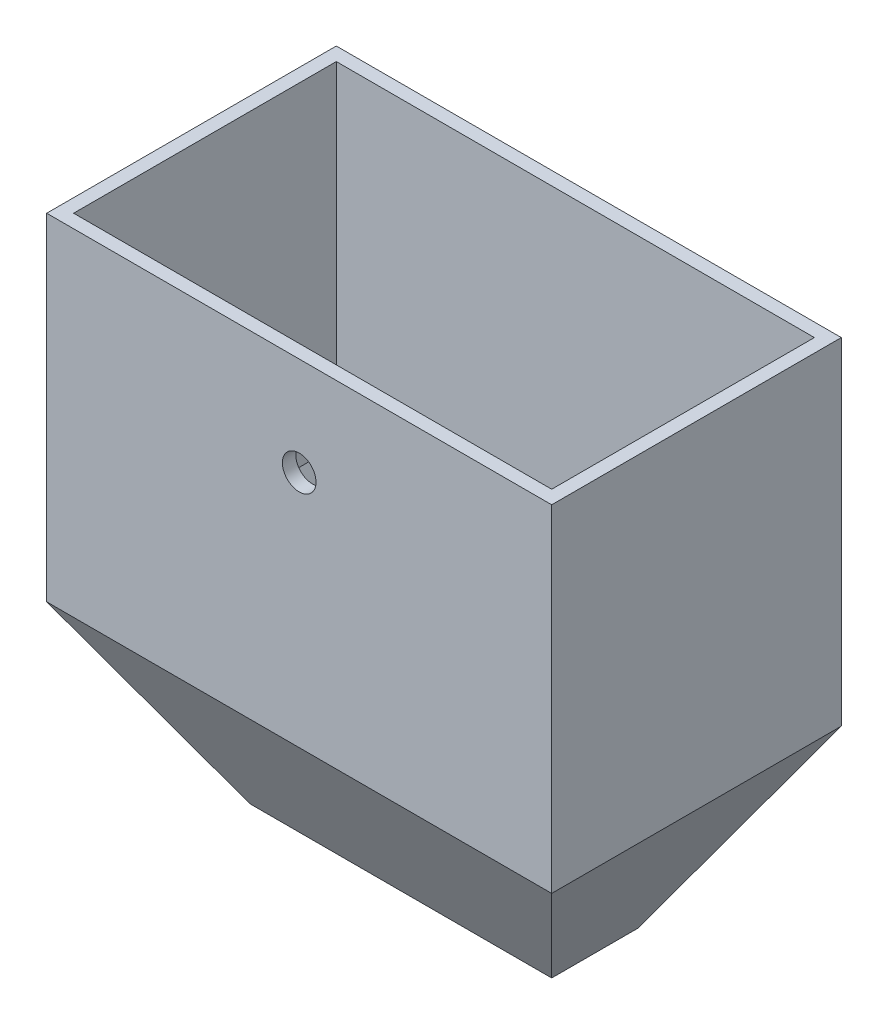
SolidWorks part; units mm, degrees
material "1.4511 (X3CrNb17)"
ref_plane "前视基准面" through (0, 0, 0) normal (0, 0, 1) x (1, 0, 0)
ref_plane "上视基准面" through (0, 0, 0) normal (0, 1, 0) x (1, 0, 0)
ref_plane "右视基准面" through (0, 0, 0) normal (1, 0, 0) x (0, 0, -1)
sketch "草图1" plane through (0, 0, 0) normal (0, 1, 0) x (1, 0, 0)
  line L1 (-187.57, 107.57) -> (187.57, 107.57)
  line L2 (-187.57, 107.57) -> (-187.57, -107.57)
  line L3 (-187.57, -107.57) -> (187.57, -107.57)
  line L4 (187.57, 107.57) -> (187.57, -107.57)
  line L5 (-187.57, 107.57) -> (187.57, -107.57) construction
  line L6 (-187.57, -107.57) -> (187.57, 107.57) construction
  point P1 (0, 0)
  dimension "D1" = 375.14
  dimension "D2" = 215.14
extrude "凸台-拉伸1" add sketch "草图1" along normal blind 250
ref_plane "基准面1" through (0, -130, 0) normal (0, 1, 0) x (1, 0, 0)
sketch "草图4" plane through (0, -130, 0) normal (0, 1, 0) x (1, 0, 0)
  line L1 (-112, 32) -> (112, 32)
  line L2 (-112, 32) -> (-112, -32)
  line L3 (-112, -32) -> (112, -32)
  line L4 (112, 32) -> (112, -32)
  line L5 (-112, 32) -> (112, -32) construction
  line L6 (-112, -32) -> (112, 32) construction
  point P0 (0, 0)
  dimension "D1" = 224
  dimension "D2" = 64
loft "放样1" add profiles "草图4" section face at (0, 0, 0) section "草图4"
shell "抽壳1" thickness 10
sketch "草图5" plane through (0, 0, 107.57) normal (0, 0, 1) x (1, 0, 0)
  line L0 (-187.57, 250) -> (187.57, 250) construction
  line L1 (-187.57, 250) -> (-187.57, 0) construction
  circle A0 centre (0, 177) radius 12.5
  dimension "D1" = 25
  dimension "D2" = 73
  dimension "D3" = 187.57
extrude "切除-拉伸1" cut sketch "草图5" against normal blind 10
sketch "草图6" plane through (0, -130, 0) normal (0, -1, 0) x (1, 0, 0)
  line L1 (-107, 27) -> (107, 27)
  line L2 (-107, 27) -> (-107, -27)
  line L3 (-107, -27) -> (107, -27)
  line L4 (107, 27) -> (107, -27)
  line L5 (-107, 27) -> (107, -27) construction
  line L6 (-107, -27) -> (107, 27) construction
  point P0 (0, 0)
  dimension "D1" = 214
  dimension "D2" = 54
extrude "切除-拉伸2" cut sketch "草图6" against normal blind 10
